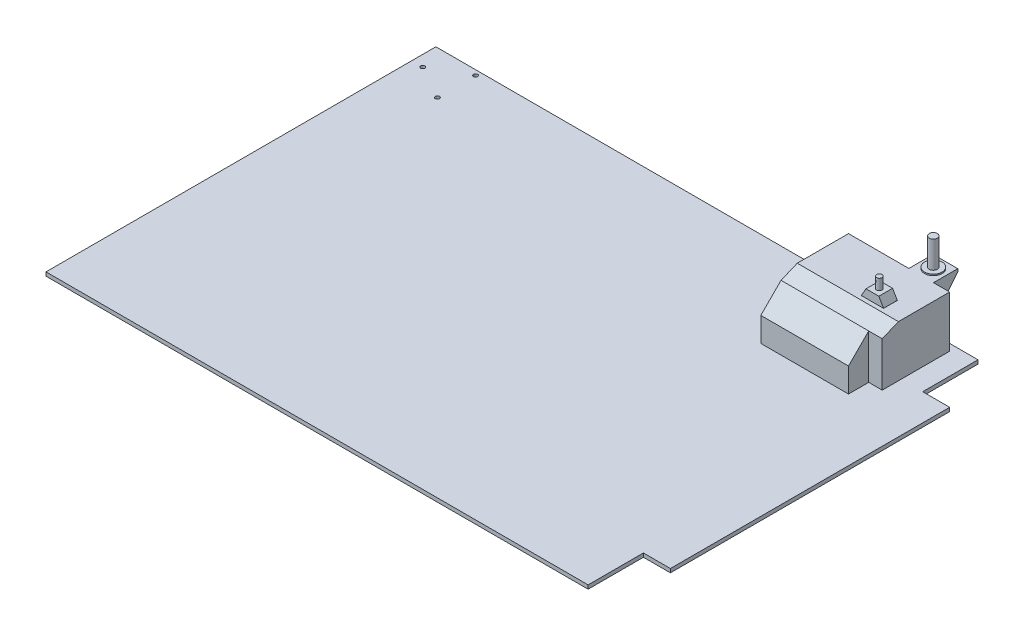
SolidWorks part; units mm, degrees
ref_plane "Alzado" through (0, 0, 0) normal (0, 0, 1) x (1, 0, 0)
ref_plane "Planta" through (0, 0, 0) normal (0, 1, 0) x (1, 0, 0)
ref_plane "Vista lateral" through (0, 0, 0) normal (1, 0, 0) x (0, 0, -1)
sketch "Croquis2" plane through (0, 0, 0) normal (0, 1, 0) x (1, 0, 0)
  line L1 (-210.93, 144.5) -> (210.93, 144.5)
  line L2 (-210.93, 144.5) -> (-210.93, -144.5)
  line L3 (-210.93, -144.5) -> (210.93, -144.5)
  line L4 (210.93, 144.5) -> (210.93, -144.5)
  line L5 (-210.93, 144.5) -> (210.93, -144.5) construction
  line L6 (-210.93, -144.5) -> (210.93, 144.5) construction
  point P0 (0, 0)
  dimension "D1" = 421.86
  dimension "D2" = 289
extrude "Saliente-Extruir1" add sketch "Croquis2" along normal blind 2.8
sketch "Croquis3" plane through (0, 2.8, 0) normal (0, 1, 0) x (1, 0, 0)
  line L0 (210.93, 144.5) -> (-210.93, 144.5) construction
  line L1 (210.93, -144.5) -> (190.93, -144.5)
  line L2 (210.93, -144.5) -> (210.93, -103.5)
  line L3 (210.93, -103.5) -> (190.93, -103.5)
  line L4 (190.93, -144.5) -> (190.93, -103.5)
  line L5 (210.93, 144.5) -> (190.93, 144.5)
  line L6 (210.93, 144.5) -> (210.93, 103.5)
  line L7 (210.93, 103.5) -> (190.93, 103.5)
  line L8 (190.93, 144.5) -> (190.93, 103.5)
  line L9 (210.93, -144.5) -> (210.93, 144.5) construction
  dimension "D1" = 41
  dimension "D2" = 20
  dimension "D3" = 41
  dimension "D4" = 20
extrude "Cortar-Extruir1" cut sketch "Croquis3" against normal blind 2.8 contours L6 L5 L8 L7 | L2 L1 L4 L3
sketch "Croquis4" plane through (0, 2.8, 0) normal (0, 1, 0) x (1, 0, 0)
  line L0 (190.93, 144.5) -> (190.93, 103.5) construction
  line L1 (174.93, 139.5) -> (99.93, 139.5)
  line L2 (174.93, 139.5) -> (174.93, 89.5)
  line L3 (174.93, 89.5) -> (164.93, 89.5)
  line L4 (99.93, 139.5) -> (99.93, 89.5)
  line L5 (190.93, 144.5) -> (-210.93, 144.5) construction
  line L6 (164.93, 89.5) -> (164.93, 74.5)
  line L7 (164.93, 74.5) -> (99.93, 74.5)
  line L8 (99.93, 74.5) -> (99.93, 89.5)
  dimension "D1" = 16
  dimension "D2" = 5
  dimension "D3" = 50
  dimension "D4" = 75
  dimension "D5" = 10
  dimension "D6" = 15
extrude "Saliente-Extruir2" add sketch "Croquis4" along normal blind 38 contours L2 L3 L6 L7 L8 L4 L1
sketch "Croquis5" plane through (174.93, 0, 0) normal (1, 0, 0) x (0, 0, -1)
  line L0 (89.5, 35.8) -> (101.5, 40.8)
  line L1 (89.5, 40.8) -> (89.5, 2.8) construction
  line L2 (139.5, 40.8) -> (89.5, 40.8) construction
  line L3 (101.5, 40.8) -> (89.5, 40.8)
  line L4 (89.5, 40.8) -> (89.5, 35.8)
  dimension "D1" = 12
  dimension "D2" = 5
extrude "Cortar-Extruir2" cut sketch "Croquis5" against normal through all
sketch "Croquis6" plane through (164.93, 0, 0) normal (1, 0, 0) x (0, 0, -1)
  line L5 (74.5, 40.8) -> (74.5, 2.8) construction
  line L6 (74.5, 35.8) -> (74.5, 20.8)
  line L7 (74.5, 20.8) -> (89.5, 35.8)
  line L10 (89.5, 35.8) -> (89.5, 40.8)
  line L11 (89.5, 40.8) -> (74.5, 40.8)
  line L12 (74.5, 35.8) -> (74.5, 40.8)
  dimension "D1" = 15
  dimension "D2" = 15
extrude "Cortar-Extruir3" cut sketch "Croquis6" against normal through all
sketch "Croquis7" plane through (0, 40.8, 0) normal (0, 1, 0) x (1, 0, 0)
  line L0 (174.93, 139.5) -> (174.93, 101.5) construction
  line L1 (160.93, 104.5) -> (144.4376, 104.5)
  line L2 (160.93, 104.5) -> (160.93, 114.6729)
  line L3 (160.93, 114.6729) -> (144.4376, 114.6729)
  line L4 (144.4376, 104.5) -> (144.4376, 114.6729)
  line L5 (174.93, 101.5) -> (99.93, 101.5) construction
  dimension "D1" = 14
  dimension "D2" = 3
extrude "Saliente-Extruir3" add sketch "Croquis7" along normal blind 6.06
chamfer "Chaflán1" distance 6 distance2 3.5 2 edges at (144.4376, 46.86, -109.5864) (160.93, 46.86, -109.5864)
sketch "Croquis9" plane through (0, 46.86, 0) normal (0, 1, 0) x (1, 0, 0)
  line L0 (147.9376, 114.6729) -> (157.43, 104.5) construction
  circle A0 centre (152.6838, 109.5864) radius 1.9955
extrude "Saliente-Extruir4" add sketch "Croquis9" along normal blind 8
sketch "Croquis10" plane through (0, 0, -139.5) normal (0, 0, -1) x (-1, 0, 0)
  line L0 (-174.93, 40.8) -> (-99.93, 40.8) construction
  line L1 (-162.93, 40.8) -> (-144.6664, 40.8)
  line L2 (-162.93, 40.8) -> (-162.93, 21.8)
  line L3 (-162.93, 21.8) -> (-144.6664, 21.8)
  line L4 (-144.6664, 40.8) -> (-144.6664, 21.8)
  line L5 (-174.93, 40.8) -> (-174.93, 2.8) construction
  dimension "D1" = 12
  dimension "D2" = 19
extrude "Saliente-Extruir5" add sketch "Croquis10" along normal blind 18 contours L2 L1 L4 L3
sketch "Croquis11" plane through (162.93, 0, 0) normal (1, 0, 0) x (0, 0, -1)
  line L0 (157.5, 38.8) -> (143.9095, 21.8)
  line L1 (157.5, 40.8) -> (157.5, 21.8) construction
  line L2 (157.5, 21.8) -> (139.5, 21.8) construction
  line L3 (143.9095, 21.8) -> (157.5, 21.8)
  line L4 (157.5, 21.8) -> (157.5, 38.8)
  dimension "D1" = 2
extrude "Cortar-Extruir4" cut sketch "Croquis11" against normal through all
sketch "Croquis12" plane through (0, 40.8, 0) normal (0, 1, 0) x (1, 0, 0)
  line L0 (144.6664, 139.5) -> (162.93, 139.5)
  line L1 (144.6664, 157.5) -> (162.93, 139.5)
  circle A0 centre (153.7982, 148.5) radius 6.5
  dimension "D1" = 13
extrude "Saliente-Extruir6" add sketch "Croquis12" along normal blind 1 contours L1 A0 | L1 A0
sketch "Croquis13" plane through (0, 41.8, 0) normal (0, 1, 0) x (1, 0, 0)
  circle A0 centre (153.7982, 148.5) radius 3
  dimension "D1" = 6
extrude "Saliente-Extruir7" add sketch "Croquis13" along normal blind 20
sketch "Croquis18" plane through (0, 2.8, 0) normal (0, 1, 0) x (1, 0, 0)
  line L0 (-165.7811, 112.4907) -> (-177.7811, 112.4907) construction
  line L1 (-215.7811, 126.6407) -> (-202.7811, 126.6407) construction
  circle A0 centre (-177.7811, 112.4907) radius 1.55
  circle A1 centre (-177.7811, 140.7907) radius 1.55
  circle A2 centre (-202.7811, 126.6407) radius 1.55
  dimension "D2" = 3.1
  dimension "D1" = 12
  dimension "D3" = 13
extrude "Cortar-Extruir5" cut sketch "Croquis18" against normal blind 10
